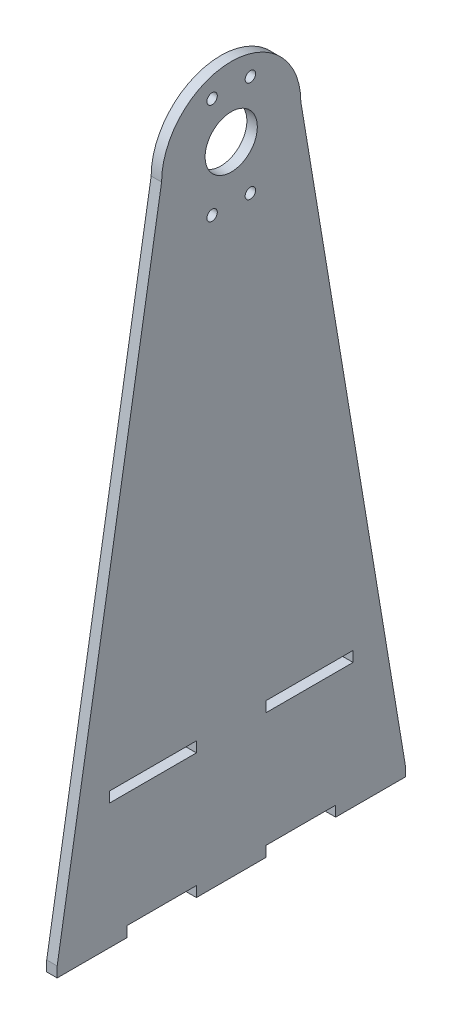
SolidWorks part; units mm, degrees
ref_plane "Alzado" through (0, 0, 0) normal (0, 0, 1) x (1, 0, 0)
ref_plane "Planta" through (0, 0, 0) normal (0, 1, 0) x (1, 0, 0)
ref_plane "Vista lateral" through (0, 0, 0) normal (1, 0, 0) x (0, 0, -1)
sketch "Sketch2" plane through (0, 0, 0) normal (1, 0, 0) x (0, 0, -1)
  line L0 (0, 0) -> (50, 0) construction
  line L1 (50, 0) -> (-50, 0)
  line L2 (0, 0) -> (0, 160) construction
  line L3 (-50, 0) -> (-20, 180)
  line L4 (50, 0) -> (20, 180)
  line L5 (0, 172.5) -> (0, 180) construction
  arc A0 (20, 180) -> (-20, 180) centre (0, 180) ccw
  circle A1 centre (0, 180) radius 7.5
  dimension "D1" = 50
  dimension "D2" = 100
  dimension "D3" = 180
extrude "Boss-Extrude1" add sketch "Sketch2" along normal mid plane 3
sketch "Sketch3" plane through (-1.5, 0, 0) normal (-1, 0, 0) x (0, 0, 1)
  line L0 (0, 0) -> (0, 33) construction
  line L4 (35, 36) -> (35, 33)
  line L5 (10, 33) -> (35, 33)
  line L8 (-10, 36) -> (-35, 36)
  line L9 (10, 36) -> (10, 33)
  line L10 (10, 36) -> (35, 36)
  line L11 (-10, 36) -> (-10, 33)
  line L12 (-10, 33) -> (-35, 33)
  line L13 (-35, 36) -> (-35, 33)
  dimension "D1" = 33
  dimension "D2" = 3
extrude "Cut-Extrude1" cut sketch "Sketch3" against normal blind 4
sketch "Sketch4" plane through (0, 0, 0) normal (0, -1, 0) x (1, 0, 0)
  line L0 (1.5, 50) -> (-1.5, 50)
  line L1 (-1.5, 50) -> (-1.5, 30)
  line L2 (-1.5, 30) -> (1.5, 30)
  line L3 (1.5, 30) -> (1.5, 50)
  line L4 (-1.5, 10) -> (-1.5, -10)
  line L5 (-1.5, -10) -> (1.5, -10)
  line L6 (1.5, -10) -> (1.5, 10)
  line L7 (1.5, 10) -> (-1.5, 10)
  line L8 (-1.5, -50) -> (1.5, -50)
  line L9 (1.5, -50) -> (1.5, -30)
  line L10 (1.5, -30) -> (-1.5, -30)
  line L11 (-1.5, -30) -> (-1.5, -50)
  line M6 (-1.5, 50) -> (-1.5, -50)
  line M7 (-1.5, -50) -> (1.5, -50)
  line M8 (1.5, -50) -> (1.5, 50)
  dimension "D1" = 20
  dimension "D2" = 20
  dimension "D3" = 20
  dimension "D4" = 20
extrude "Boss-Extrude2" add sketch "Sketch4" along normal blind 3 contours L7 L5 M8 M6 | L10 M8 M6 M7 | L1 L2 L3 L0
sketch "Sketch5" plane through (1.5, 0, 0) normal (1, 0, 0) x (0, 0, -1)
  line L0 (0, 180) -> (0, 195)
  line L1 (0, 195) -> (7, 195) construction
  line L2 (0, 195) -> (-7, 195) construction
  line L3 (-7, 195) -> (-5.5, 195) construction
  line L4 (-5.5, 195) -> (-5.5, 193.5) construction
  line L5 (0, 195) -> (0, 163) construction
  line L6 (0, 163) -> (0, 179) construction
  line L7 (0, 179) -> (16.2909, 179) construction
  circle A0 centre (-5.5, 193.5) radius 1.5
  circle A1 centre (5.5, 193.5) radius 1.5
  circle A2 centre (-5.5, 164.5) radius 1.5
  circle A3 centre (5.5, 164.5) radius 1.5
  dimension "D1" = 7
  dimension "D2" = 7
  dimension "D3" = 1.5
  dimension "D4" = 1.5
  dimension "D5" = 32
extrude "Cut-Extrude2" cut sketch "Sketch5" against normal blind 10 contours A0 | A2 | A3 | A1
